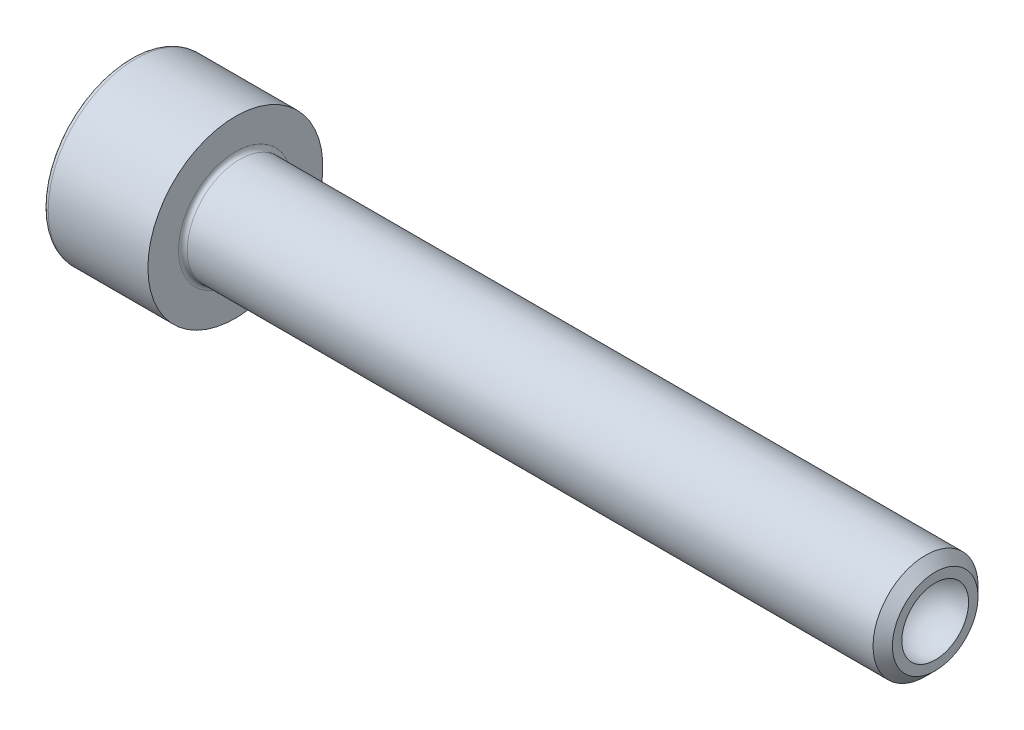
SolidWorks part; units mm, degrees
ref_plane "Plane1" through (0, 0, 0) normal (0, 0, 1) x (1, 0, 0)
ref_plane "Plane2" through (0, 0, 0) normal (0, 1, 0) x (1, 0, 0)
ref_plane "Plane3" through (0, 0, 0) normal (1, 0, 0) x (0, 0, -1)
sketch "BodySke" plane through (0, 0, 0) normal (0, 0, 1) x (1, 0, 0)
  line L0 (0, 0) -> (0, 5)
  line L1 (0, 5) -> (6, 5)
  line L2 (6, 5) -> (6, 3)
  line L3 (6, 3) -> (45.4455, 3)
  line L4 (46, 2.4455) -> (46, 0)
  line L5 (46, 0) -> (0, 0)
  line L6 (-31.75, 0) -> (127, 0) construction
  line L8 (46, 2.4455) -> (45.4455, 3)
  line L10 (46, -2.4455) -> (45.4455, -3) construction
  line L11 (7, 9.525) -> (7, 3.175) construction
  line L12 (6, 9.525) -> (6, 3.175) construction
  line L13 (-14, 9.525) -> (-14, 3.175) construction
  dimension "Diameter" = 6
  dimension "Head_ht" = 6
  dimension "Length" = 40
  dimension "Body_ch_ang" = 45
  dimension "Head_dia" = 10
  dimension "Minor_dia" = 4.891
  dimension "Advance" = 1
  dimension "Thread_nom" = 40
  dimension "Thread_length" = 60
revolve "Base-Revolve" add sketch "BodySke"
cosmetic thread "ThreadCosmetic" [suppressed]
fillet "Fillet1" radius 0.25 1 edges at (6, 0, 3)
fillet "Fillet2" radius 0.3 1 edges at (0, 0, 5)
sketch "Sketch2" plane through (0, 0, 0) normal (0, 0, 1) x (1, 0, 0)
  line L0 (0, 2.542) -> (3, 2.542)
  line L1 (3, 2.542) -> (4.4676, 0)
  line L2 (-31.75, 0) -> (127, 0) construction
  line L3 (4.4676, 0) -> (0, 0)
  line L4 (0, 0) -> (0, 2.542)
  line L6 (0, 0) -> (47.625, 0) construction
  dimension "D1" = 2.542
  dimension "D2" = 60
  dimension "Depth" = 3
revolve "Hex-PreBroach" cut sketch "Sketch2" angle 360 about L6
sketch "Sketch3" plane through (0, 0, 0) normal (-1, 0, 0) x (0, 0.5, 0.866)
  line L0 (1.4676, 2.542) -> (-1.4676, 2.542)
  line L1 (-1.4676, 2.542) -> (-2.9352, 0)
  line L2 (1.4676, 2.542) -> (2.9352, 0)
  line L3 (1.4676, -2.542) -> (2.9352, 0)
  line L4 (1.4676, -2.542) -> (-1.4676, -2.542)
  line L5 (-1.4676, -2.542) -> (-2.9352, 0)
  dimension "D1" = 2.542
  dimension "D2" = 2.542
  dimension "Hex_size" = 5.084
extrude "Hex" cut sketch "Sketch3" against normal blind 3
sketch "ThdSchSke" plane through (0, 0, 0) normal (0, 0, 1) x (1, 0, 0)
  line L0 (9, -2.4455) -> (8.6117, -3)
  line L1 (9, -2.4455) -> (9.3883, -3)
  line L2 (9.3883, -3) -> (9.3883, -3.75)
  line L3 (-3.175, 0) -> (5.1513, 0) construction
  line L4 (0, 4.7) -> (0, -4.7) construction
  line L5 (9.3883, -3.75) -> (8.6117, -3.75)
  line L6 (8.6117, -3.75) -> (8.6117, -3)
  dimension "Thread_minor" = 4.891
  dimension "Diameter" = 6
  dimension "Start" = 9
  dimension "SideAngle" = 55
  dimension "VeeAngle" = 70
  dimension "Overcut" = 7.5
revolve "ThreadSchematic" [suppressed] cut sketch "ThdSchSke" angle 360 about L3
pattern_linear "ThdSchPat" [suppressed]
sketch "Esquisse3" plane through (0, 0, 0) normal (0, 0, 1) x (1, 0, 0)
  line L0 (47.6705, 0) -> (34.7818, 0) construction
  line L1 (46, -2.4455) -> (46, 2.4455) construction
  line L2 (46, 2.4455) -> (46, -2.4455) construction
  line L4 (43.4, 0) -> (46, 0)
  line L5 (46, 0) -> (46, -1.9079)
  arc A0 (43.4, 0) -> (46, -1.9079) centre (45.4, 0) ccw
  dimension "D1" = 2.6
  dimension "D2" = 2
revolve "Enlèvement de matière-Révolution1" cut sketch "Esquisse3" angle 360 about L4
equation "\"D2@Sketch3\" = \"Hex_size@Sketch3\" / 2"
equation "\"D1@Sketch3\" = \"Hex_size@Sketch3\" / 2"
equation "\"D1@Sketch2\" = \"Hex_size@Sketch3\" / 2"
equation "\"Thread_minor@ThreadCosmetic\"  =  \"Minor_dia@BodySke\""
equation "\"Depth@Sketch2\" =  \"Key_eng@Hex\""
equation "\"Thread_length@ThreadCosmetic\" = ((sgn( (\"Length@BodySke\" - \"Advance@BodySke\" * 3.0) - \"Thread_nom@BodySke\" )-1)*( (\"Length@BodySke\" - \"Advance@BodySke\" * 3.0) - \"Thread_nom@BodySke\" ))/-2+ \"Thread_nom@BodySke\""
equation "\"Thread_minor@ThdSchSke\" = \"Minor_dia@BodySke\""
equation "\"Diameter@ThdSchSke\" = \"Diameter@BodySke\""
equation "\"Overcut@ThdSchSke\" = \"Diameter@BodySke\" * 1.25"
equation "\"Start@ThdSchSke\" = \"Head_ht@BodySke\" + \"Length@BodySke\" - \"Thread_length@ThreadCosmetic\"  '---Non-countersunk---"
equation "\"Num_threads@ThdSchPat\" = int( \"Thread_length@ThreadCosmetic\" / \"Advance@BodySke\" + 0.999 )  + 1"
equation "\"Advance@ThdSchPat\" = \"Thread_length@ThreadCosmetic\" /  (\"Num_threads@ThdSchPat\" - 1) 'relax it"
equation "\"Num_threads@ThdSchPat\" = \"Num_threads@ThdSchPat\" - sgn( \"Num_threads@ThdSchPat\" - 1) '---chamfered tips only---"
